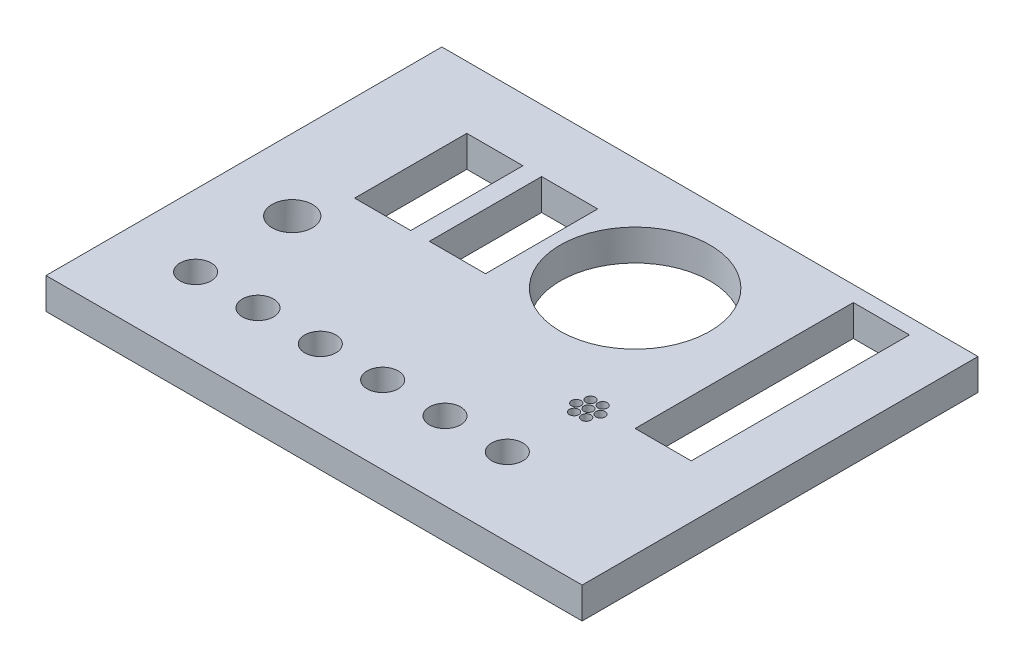
SolidWorks part; units mm, degrees
ref_plane "Přední rovina" through (0, 0, 0) normal (0, 0, 1) x (1, 0, 0)
ref_plane "Horní rovina" through (0, 0, 0) normal (0, 1, 0) x (1, 0, 0)
ref_plane "Pravá rovina" through (0, 0, 0) normal (1, 0, 0) x (0, 0, -1)
sketch "Skica2" plane through (0, 0, 0) normal (0, 1, 0) x (1, 0, 0)
  line L1 (-43, -31.75) -> (43, -31.75)
  line L2 (-43, -31.75) -> (-43, 31.75)
  line L3 (-43, 31.75) -> (43, 31.75)
  line L4 (43, -31.75) -> (43, 31.75)
  line L5 (-43, -31.75) -> (43, 31.75) construction
  line L6 (-43, 31.75) -> (43, -31.75) construction
  point P0 (0, 0)
  dimension "D1" = 86
  dimension "D2" = 63.5
extrude "Přidat vysunutím1" add sketch "Skica2" along normal blind 5
sketch "Skica4" plane through (0, 5, 0) normal (0, 1, 0) x (1, 0, 0)
  line L0 (-43, -19.25) -> (43, -19.25) construction
  line L1 (-43, 31.75) -> (-43, -31.75) construction
  line L2 (43, -31.75) -> (43, 31.75) construction
  line L3 (-43, -31.75) -> (43, -31.75) construction
  line L4 (-31.5, -19.25) -> (-31.5, -3.75) construction
  line L5 (-31.5, -3.75) -> (-43, -3.75) construction
  line L6 (-43, 21.75) -> (-21.699, 21.75) construction
  line L7 (-29, 31.75) -> (-29, 21.75) construction
  line L8 (43, 31.75) -> (-43, 31.75) construction
  line L9 (-21.699, 21.75) -> (0.6887, 21.75) construction
  line L10 (-29, 21.75) -> (-20, 21.75)
  line L11 (-29, 21.75) -> (-29, 3.75)
  line L12 (-29, 3.75) -> (-20, 3.75)
  line L13 (-20, 21.75) -> (-20, 3.75)
  line L14 (-17, 21.75) -> (-17, 13.1421) construction
  line L15 (6, 31.75) -> (6, 1.332) construction
  line L16 (-17, 21.75) -> (-8, 21.75)
  line L17 (-17, 21.75) -> (-17, 3.75)
  line L18 (-17, 3.75) -> (-8, 3.75)
  line L19 (-8, 21.75) -> (-8, 3.75)
  line L20 (6, 13.75) -> (34.5, 13.75) construction
  line L21 (43, 29.25) -> (34.5, 29.25) construction
  line L22 (34.5, 29.25) -> (34.5, 13.1421) construction
  line L23 (19, -31.75) -> (19, -6.75) construction
  line L24 (34.5, 29.25) -> (25.5, 29.25)
  line L25 (34.5, 29.25) -> (34.5, -5.75)
  line L26 (34.5, -5.75) -> (25.5, -5.75)
  line L27 (25.5, 29.25) -> (25.5, -5.75)
  line L28 (19, -6.75) -> (35.6058, -6.75) construction
  line L29 (18.314, -8.3599) -> (19.686, -5.1401) construction
  line L30 (20.7372, -6.5391) -> (17.2628, -6.9609) construction
  line L31 (20.0512, -8.1491) -> (17.9488, -5.3509) construction
  line L32 (17.9488, -5.3509) -> (19.686, -5.1401) construction
  line L33 (19.686, -5.1401) -> (20.7372, -6.5391) construction
  line L34 (20.7372, -6.5391) -> (20.0512, -8.1491) construction
  line L35 (20.0512, -8.1491) -> (18.314, -8.3599) construction
  line L36 (18.314, -8.3599) -> (17.2628, -6.9609) construction
  line L37 (17.2628, -6.9609) -> (17.9488, -5.3509) construction
  circle A0 centre (-31.5, -19.25) radius 2.5
  circle A1 centre (-21.5, -19.25) radius 2.5
  circle A2 centre (-11.5, -19.25) radius 2.5
  circle A3 centre (-1.5, -19.25) radius 2.5
  circle A4 centre (8.5, -19.25) radius 2.5
  circle A5 centre (18.5, -19.25) radius 2.5
  circle A6 centre (-31.5, -3.75) radius 3.25
  circle A7 centre (6, 13.75) radius 12
  circle A8 centre (19, -6.75) radius 2.5 construction
  circle A10 centre (17.9488, -5.3509) radius 0.75
  circle A11 centre (19, -6.75) radius 0.75
  circle A12 centre (19.686, -5.1401) radius 0.75
  circle A13 centre (20.7372, -6.5391) radius 0.75
  circle A14 centre (20.0512, -8.1491) radius 0.75
  circle A15 centre (18.314, -8.3599) radius 0.75
  circle A16 centre (17.2628, -6.9609) radius 0.75
  point P9 (18.6933, -5.2606)
  point P30 (-29, 21.75)
  point P45 (-6, 13.75)
  point P56 (16.5128, -6.9609)
  point P60 (18.9415, -5.2304)
  point P61 (18.3993, -5.9505)
  point P62 (18.5495, -6.1504)
  point P73 (19, -6.75)
  point P74 (18.3993, -5.9505)
  point P75 (18.5495, -6.1504)
  dimension "D3" = 5
  dimension "D8" = 6.5
  dimension "D19" = 24
  dimension "D20" = 2
  dimension "D27" = 5
  dimension "D28" = 1.5
  dimension "D29" = 1.5
  dimension "D30" = 6
  dimension "D32" = 0.2482
  dimension "D34" = 19.5
  dimension "D1" = 12.5
  dimension "D2" = 11.5
  dimension "D5" = 61.5
  dimension "D6" = 10
  dimension "D7" = 28
  dimension "D9" = 14
  dimension "D10" = 10
  dimension "D11" = 18
  dimension "D12" = 9
  dimension "D13" = 26
  dimension "D14" = 9
  dimension "D15" = 18
  dimension "D16" = 3
  dimension "D17" = 18
  dimension "D18" = 49
  dimension "D21" = 2.5
  dimension "D22" = 8.5
  dimension "D23" = 9
  dimension "D24" = 35
  dimension "D25" = 25
  dimension "D26" = 24
  dimension "D31" = 1.75
  dimension "D33" = 0.25
  dimension "D4" = 6
extrude "Odebrat vysunutím1" cut sketch "Skica4" against normal up to next
